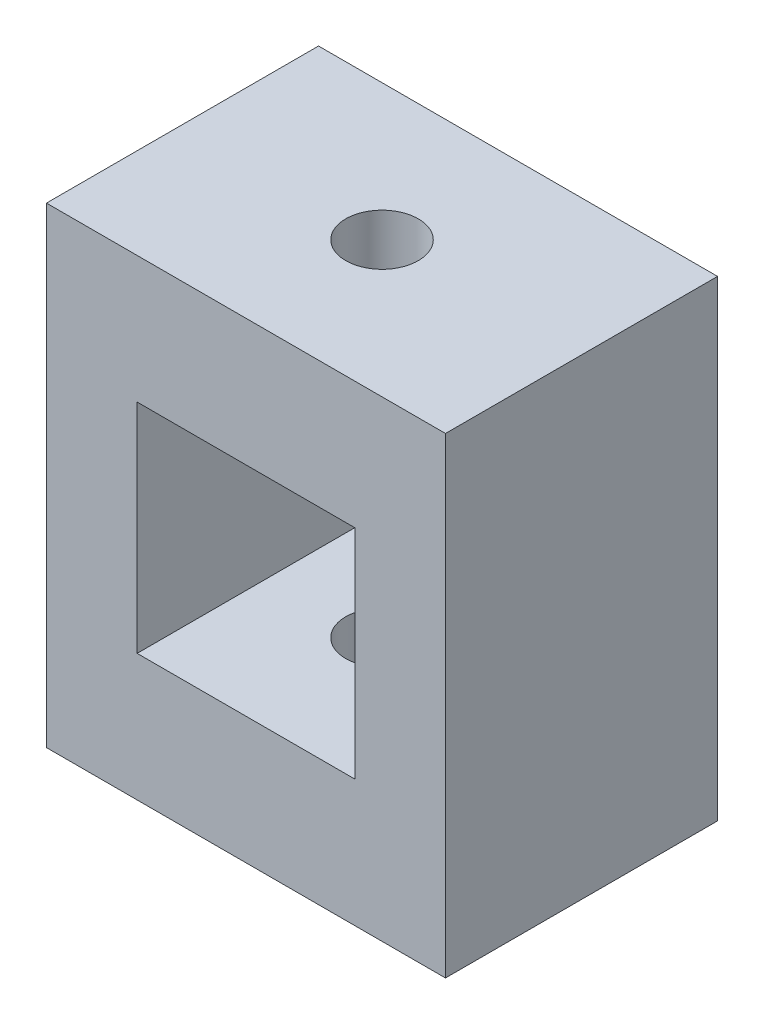
SolidWorks part; units mm, degrees
ref_plane "Front Plane" through (0, 0, 0) normal (0, 0, 1) x (1, 0, 0)
ref_plane "Top Plane" through (0, 0, 0) normal (0, 1, 0) x (1, 0, 0)
ref_plane "Right Plane" through (0, 0, 0) normal (1, 0, 0) x (0, 0, -1)
sketch "Sketch1" plane through (0, 0, 0) normal (0, 0, 1) x (1, 0, 0)
  line L1 (0, 0) -> (22, 0)
  line L2 (0, 0) -> (0, 26)
  line L3 (0, 26) -> (22, 26)
  line L4 (22, 0) -> (22, 26)
  line L5 (5, 7) -> (17, 7)
  line L6 (5, 7) -> (5, 19)
  line L7 (5, 19) -> (17, 19)
  line L8 (17, 7) -> (17, 19)
  point P9 (5, 13)
  point P10 (0, 13)
  point P11 (11, 7)
  point P12 (11, 0)
  dimension "D1" = 12
  dimension "D2" = 22
  dimension "D3" = 7
  dimension "D4" = 7
extrude "Boss-Extrude1" add sketch "Sketch1" along normal blind 15
sketch "Sketch2" plane through (0, 26, 0) normal (0, 1, 0) x (1, 0, 0)
  line L0 (0, -15) -> (0, 0) construction
  line L1 (22, -15) -> (0, -15) construction
  circle A0 centre (11, -7.5) radius 2
  point P4 (0, -7.5)
  point P7 (11, -15)
  dimension "D1" = 4
extrude "Cut-Extrude1" cut sketch "Sketch2" against normal blind 42
